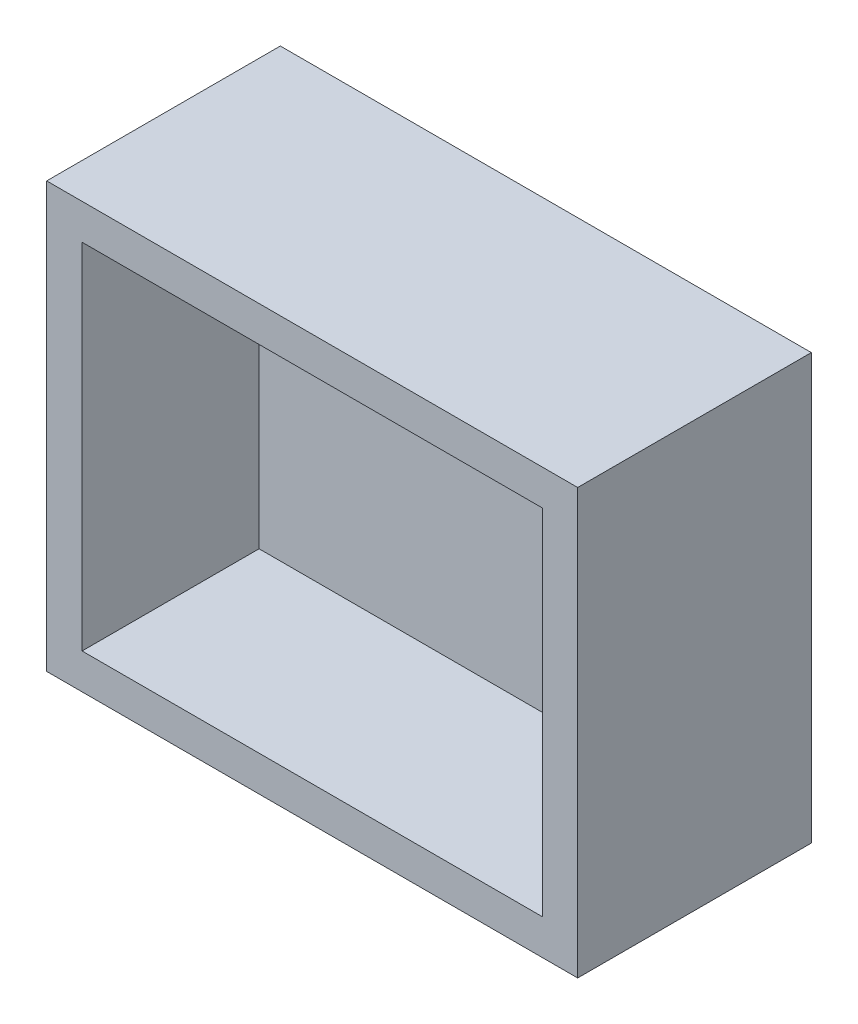
SolidWorks part; units mm, degrees
ref_plane "Front Plane" through (0, 0, 0) normal (0, 0, 1) x (1, 0, 0)
ref_plane "Top Plane" through (0, 0, 0) normal (0, 1, 0) x (1, 0, 0)
ref_plane "Right Plane" through (0, 0, 0) normal (1, 0, 0) x (0, 0, -1)
sketch "Esquisse1" plane through (0, 0, 0) normal (0, 0, 1) x (1, 0, 0)
  line L1 (-37.5, -30) -> (37.5, -30)
  line L2 (-37.5, -30) -> (-37.5, 30)
  line L3 (-37.5, 30) -> (37.5, 30)
  line L4 (37.5, -30) -> (37.5, 30)
  line L5 (-37.5, -30) -> (37.5, 30) construction
  line L6 (-37.5, 30) -> (37.5, -30) construction
  point P0 (0, 0)
  dimension "D1" = 75
  dimension "D2" = 60
extrude "Boss.-Extru.1" add sketch "Esquisse1" against normal blind 8
sketch "Esquisse2" plane through (0, 0, 0) normal (0, 0, 1) x (1, 0, 0)
  line L1 (-20, 22.5) -> (20, 22.5)
  line L2 (-20, 22.5) -> (-20, 2.5)
  line L3 (-20, 2.5) -> (20, 2.5)
  line L4 (20, 22.5) -> (20, 2.5)
  point P4 (0, 22.5)
  dimension "D1" = 40
  dimension "D2" = 20
  dimension "D3" = 2.5
extrude "Enlèv. mat.-Extru.1" cut sketch "Esquisse2" against normal blind 8
sketch "Esquisse3" plane through (0, 0, 0) normal (0, 0, 1) x (1, 0, 0)
  line L0 (-20, 11.25) -> (-28.5, 11.25)
  line L1 (-20, 22.5) -> (-20, 2.5) construction
  line L2 (-28.5, 11.25) -> (-28.5, 13.75)
  line L3 (-28.5, 13.75) -> (-20, 13.75)
  line L4 (-20, 13.75) -> (-20, 11.25)
  line L5 (-20, 12.5) -> (20, 12.5) construction
  line L6 (20, 2.5) -> (20, 22.5) construction
  point P10 (-20, 12.5)
  dimension "D1" = 2.5
  dimension "D2" = 8.5
extrude "Enlèv. mat.-Extru.2" cut sketch "Esquisse3" against normal blind 8
sketch "Esquisse4" plane through (0, 0, 0) normal (0, 0, 1) x (1, 0, 0)
  line L0 (-28.5, 12.5) -> (-4.9147, 12.5) construction
  line L1 (-28.5, 13.75) -> (-28.5, 11.25) construction
  line L2 (-20, 22.5) -> (-20, 13.75) construction
  circle A0 centre (-24, 17.5) radius 2.7
  circle A1 centre (-24, 7.5) radius 2.7
  dimension "D1" = 5.4
  dimension "D2" = 5.4
  dimension "D3" = 10
  dimension "D4" = 5
  dimension "D5" = 4
extrude "Enlèv. mat.-Extru.3" cut sketch "Esquisse4" against normal through all
mirror "Symétrie2" about plane through (0, 0, 0) normal (1, 0, 0) of "Enlèv. mat.-Extru.2", "Enlèv. mat.-Extru.3"
sketch "Esquisse6" plane through (0, 0, 0) normal (0, 0, 1) x (1, 0, 0)
  line L1 (-37.5, 30) -> (37.5, 30)
  line L2 (-37.5, 30) -> (-37.5, -30)
  line L3 (-37.5, -30) -> (37.5, -30)
  line L4 (37.5, 30) -> (37.5, -30)
extrude "Boss.-Extru.2" add sketch "Esquisse6" along normal blind 35
sketch "Esquisse7" plane through (0, 0, 35) normal (0, 0, 1) x (1, 0, 0)
  line L0 (-37.5, 30) -> (-37.5, -30) construction
  line L1 (32.5, -25) -> (-32.5, -25)
  line L2 (32.5, -25) -> (32.5, 25)
  line L3 (32.5, 25) -> (-32.5, 25)
  line L4 (-32.5, -25) -> (-32.5, 25)
  line L5 (32.5, -25) -> (-32.5, 25) construction
  line L6 (32.5, 25) -> (-32.5, -25) construction
  line L7 (37.5, 30) -> (-37.5, 30) construction
  point P0 (0, 0)
  dimension "D1" = 5
  dimension "D2" = 5
extrude "Enlèv. mat.-Extru.4" cut sketch "Esquisse7" against normal blind 35
sketch "Sketch1" plane through (37.5, 0, 0) normal (1, 0, 0) x (0, 0, -1)
  line L0 (8, -30) -> (-35, -30) construction
  line L1 (-35, 30) -> (-25, 30)
  line L2 (-35, 30) -> (-35, -30)
  line L3 (-35, -30) -> (-25, -30)
  line L4 (-25, 30) -> (-25, -30)
  dimension "D1" = 10
extrude "Cut-Extrude1" cut sketch "Sketch1" against normal up to surface (75 mm away) up to face at (-37.5, 0, 13.5)
